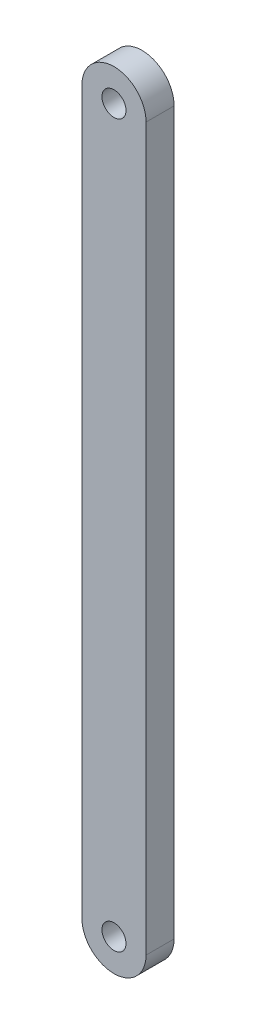
SolidWorks part; units mm, degrees
material "Balsa"
ref_plane "Front Plane" through (0, 0, 0) normal (0, 0, 1) x (1, 0, 0)
ref_plane "Top Plane" through (0, 0, 0) normal (0, 1, 0) x (1, 0, 0)
ref_plane "Right Plane" through (0, 0, 0) normal (1, 0, 0) x (0, 0, -1)
sketch "Sketch1" plane through (0, 0, 0) normal (0, 0, 1) x (1, 0, 0)
  line L0 (0, 0) -> (0, 90) construction
  line L1 (-4, 90) -> (-4, 0)
  line L2 (4, 0) -> (4, 90)
  arc A0 (-4, 90) -> (4, 90) centre (0, 90) cw
  arc A1 (-4, 0) -> (4, 0) centre (0, 0) ccw
  circle A2 centre (0, 90) radius 1.5
  circle A3 centre (0, 0) radius 1.5
  dimension "D2" = 4
  dimension "D3" = 3
  dimension "D1" = 90
extrude "Boss-Extrude1" add sketch "Sketch1" along normal blind 3.5
